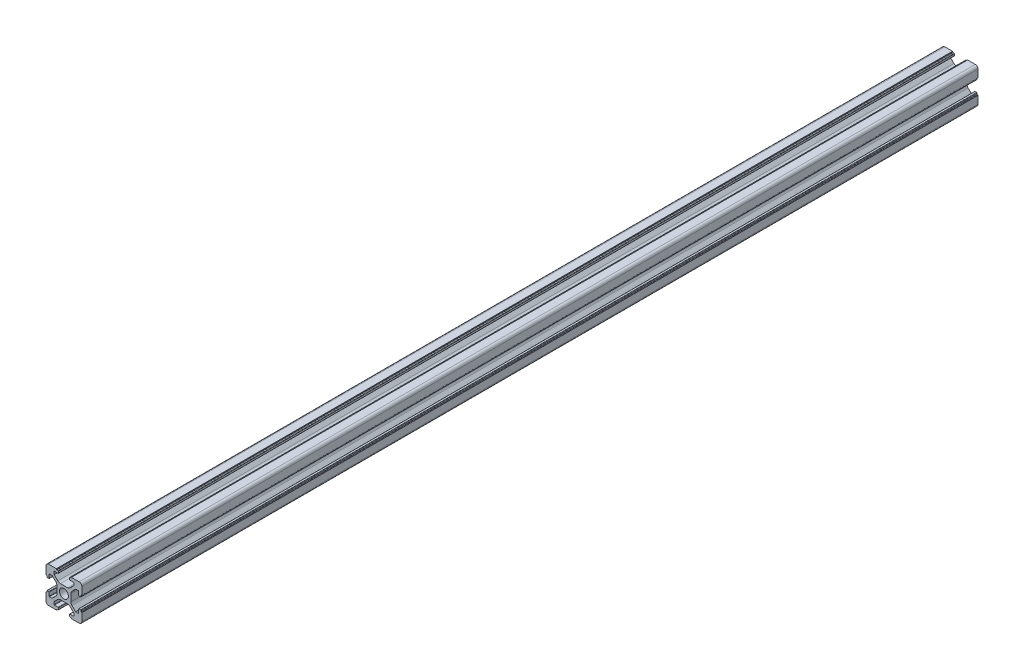
SolidWorks part; units mm, degrees
material "6063-T5"
ref_plane "Front Plane" through (0, 0, 0) normal (0, 0, 1) x (1, 0, 0)
ref_plane "Top Plane" through (0, 0, 0) normal (0, 1, 0) x (1, 0, 0)
ref_plane "Right Plane" through (0, 0, 0) normal (1, 0, 0) x (0, 0, -1)
sketch "Sketch1" plane through (0, 0, 0) normal (0, 0, -1) x (1, 0, 0)
  line L0 (1.5, 0) -> (5.8, 0)
  line L1 (20, 1.5) -> (20, 5.8)
  line L2 (18.5, 20) -> (14.2, 20)
  line L3 (0, 18.5) -> (0, 14.2)
  line L4 (14.2, 0) -> (18.5, 0)
  line L5 (13.3, 18.2) -> (15.3, 18.2)
  line L6 (20, 14.2) -> (20, 18.5)
  line L7 (0, 5.8) -> (0, 1.5)
  line L8 (6.7, 18.2) -> (4.7, 18.2)
  line L9 (1.8, 13.3) -> (1.8, 15.3)
  line L10 (19.3, 13.1) -> (18.4, 13.1)
  line L11 (19.3, 6.9) -> (18.4, 6.9)
  line L12 (6.9, 19.3) -> (6.9, 18.4)
  line L13 (13.1, 19.3) -> (13.1, 18.4)
  line L14 (0.7, 13.1) -> (1.6, 13.1)
  line L15 (0.7, 6.9) -> (1.6, 6.9)
  line L16 (13.4251, 14.4858) -> (15.4121, 16.4728)
  line L17 (14.4858, 13.4251) -> (16.4728, 15.4121)
  line L18 (14.4858, 6.5749) -> (16.4728, 4.5879)
  line L19 (13.4251, 5.5142) -> (15.4121, 3.5272)
  line L20 (6.5749, 5.5142) -> (4.5879, 3.5272)
  line L21 (5.5142, 6.5749) -> (3.5272, 4.5879)
  line L22 (5.5142, 13.4251) -> (3.5272, 15.4121)
  line L23 (6.5749, 14.4858) -> (4.5879, 16.4728)
  line L24 (6.9, 0.7) -> (6.9, 1.6)
  line L25 (13.1, 0.7) -> (13.1, 1.6)
  line L26 (5.8, 20) -> (1.5, 20)
  line L27 (1.8, 6.7) -> (1.8, 4.7)
  line L28 (6.7, 1.8) -> (4.7, 1.8)
  line L29 (13.3, 1.8) -> (15.3, 1.8)
  line L30 (18.2, 13.3) -> (18.2, 15.3)
  line L31 (18.2, 6.7) -> (18.2, 4.7)
  line L32 (2, 4.5) -> (3.3151, 4.5)
  line L33 (2, 15.5) -> (3.3151, 15.5)
  line L34 (4.5, 18) -> (4.5, 16.6849)
  line L35 (15.5, 18) -> (15.5, 16.6849)
  line L36 (18, 15.5) -> (16.6849, 15.5)
  line L37 (4.5, 2) -> (4.5, 3.3151)
  line L38 (15.5, 2) -> (15.5, 3.3151)
  line L39 (18, 4.5) -> (16.6849, 4.5)
  line L40 (7.9891, 13.9) -> (12.0109, 13.9)
  line L41 (7.9891, 6.1) -> (12.0109, 6.1)
  line L42 (13.9, 12.0109) -> (13.9, 7.9891)
  line L43 (6.1, 12.0109) -> (6.1, 7.9891)
  line L44 (19.5, 6.7) -> (19.5, 6.1)
  line L45 (5.9, 19.9) -> (5.9, 19.7)
  line L46 (6.1, 19.5) -> (6.7, 19.5)
  line L47 (14.1, 19.9) -> (14.1, 19.7)
  line L48 (13.9, 19.5) -> (13.3, 19.5)
  line L49 (0.1, 14.1) -> (0.3, 14.1)
  line L50 (0.5, 13.9) -> (0.5, 13.3)
  line L51 (0.1, 5.9) -> (0.3, 5.9)
  line L52 (0.5, 6.1) -> (0.5, 6.7)
  line L53 (19.9, 14.1) -> (19.7, 14.1)
  line L54 (19.5, 13.9) -> (19.5, 13.3)
  line L55 (19.7, 5.9) -> (19.9, 5.9)
  line L56 (14.1, 0.1) -> (14.1, 0.3)
  line L57 (13.9, 0.5) -> (13.3, 0.5)
  line L58 (6.7, 0.5) -> (6.1, 0.5)
  line L59 (5.9, 0.3) -> (5.9, 0.1)
  circle A0 centre (10, 10) radius 2.5
  arc A1 (18.5, 0) -> (20, 1.5) centre (18.5, 1.5) ccw
  arc A2 (1.5, 0) -> (0, 1.5) centre (1.5, 1.5) cw
  arc A3 (20, 18.5) -> (18.5, 20) centre (18.5, 18.5) ccw
  arc A4 (1.5, 20) -> (0, 18.5) centre (1.5, 18.5) ccw
  arc A5 (12.0109, 6.1) -> (13.4251, 5.5142) centre (12.0109, 4.1) cw
  arc A6 (13.9, 7.9891) -> (14.4858, 6.5749) centre (15.9, 7.9891) ccw
  arc A7 (13.9, 12.0109) -> (14.4858, 13.4251) centre (15.9, 12.0109) cw
  arc A8 (12.0109, 13.9) -> (13.4251, 14.4858) centre (12.0109, 15.9) ccw
  arc A9 (7.9891, 13.9) -> (6.5749, 14.4858) centre (7.9891, 15.9) cw
  arc A10 (6.1, 7.9891) -> (5.5142, 6.5749) centre (4.1, 7.9891) cw
  arc A11 (6.1, 12.0109) -> (5.5142, 13.4251) centre (4.1, 12.0109) ccw
  arc A12 (13.1, 1.6) -> (13.3, 1.8) centre (13.3, 1.6) cw
  arc A13 (6.9, 1.6) -> (6.7, 1.8) centre (6.7, 1.6) ccw
  arc A14 (6.1, 0.5) -> (5.9, 0.3) centre (6.1, 0.3) ccw
  arc A15 (6.7, 0.5) -> (6.9, 0.7) centre (6.7, 0.7) ccw
  arc A16 (1.6, 6.9) -> (1.8, 6.7) centre (1.6, 6.7) cw
  arc A17 (0.5, 6.7) -> (0.7, 6.9) centre (0.7, 6.7) cw
  arc A18 (0.5, 13.3) -> (0.7, 13.1) centre (0.7, 13.3) ccw
  arc A19 (1.6, 13.1) -> (1.8, 13.3) centre (1.6, 13.3) ccw
  arc A20 (6.7, 19.5) -> (6.9, 19.3) centre (6.7, 19.3) cw
  arc A21 (6.9, 18.4) -> (6.7, 18.2) centre (6.7, 18.4) cw
  arc A22 (13.1, 18.4) -> (13.3, 18.2) centre (13.3, 18.4) ccw
  arc A23 (13.3, 19.5) -> (13.1, 19.3) centre (13.3, 19.3) ccw
  arc A24 (18.4, 13.1) -> (18.2, 13.3) centre (18.4, 13.3) cw
  arc A25 (19.5, 13.3) -> (19.3, 13.1) centre (19.3, 13.3) cw
  arc A26 (19.5, 6.7) -> (19.3, 6.9) centre (19.3, 6.7) ccw
  arc A27 (14.1, 0.3) -> (13.9, 0.5) centre (13.9, 0.3) ccw
  arc A28 (19.5, 6.1) -> (19.7, 5.9) centre (19.7, 6.1) ccw
  arc A29 (5.9, 19.7) -> (6.1, 19.5) centre (6.1, 19.7) ccw
  arc A30 (14.1, 19.7) -> (13.9, 19.5) centre (13.9, 19.7) cw
  arc A31 (19.7, 14.1) -> (19.5, 13.9) centre (19.7, 13.9) ccw
  arc A32 (13.3, 0.5) -> (13.1, 0.7) centre (13.3, 0.7) cw
  arc A33 (0.3, 14.1) -> (0.5, 13.9) centre (0.3, 13.9) cw
  arc A34 (0.3, 5.9) -> (0.5, 6.1) centre (0.3, 6.1) ccw
  arc A35 (0, 5.8) -> (0.1, 5.9) centre (0.1, 5.8) cw
  arc A36 (5.9, 0.1) -> (5.8, 0) centre (5.8, 0.1) cw
  arc A37 (14.1, 0.1) -> (14.2, 0) centre (14.2, 0.1) ccw
  arc A38 (19.9, 5.9) -> (20, 5.8) centre (19.9, 5.8) cw
  arc A39 (20, 14.2) -> (19.9, 14.1) centre (19.9, 14.2) cw
  arc A40 (14.2, 20) -> (14.1, 19.9) centre (14.2, 19.9) ccw
  arc A41 (5.8, 20) -> (5.9, 19.9) centre (5.8, 19.9) cw
  arc A42 (0, 14.2) -> (0.1, 14.1) centre (0.1, 14.2) ccw
  arc A43 (18.4, 6.9) -> (18.2, 6.7) centre (18.4, 6.7) ccw
  arc A44 (1.8, 15.3) -> (2, 15.5) centre (2, 15.3) cw
  arc A45 (1.8, 4.7) -> (2, 4.5) centre (2, 4.7) ccw
  arc A46 (4.7, 1.8) -> (4.5, 2) centre (4.7, 2) cw
  arc A47 (15.3, 1.8) -> (15.5, 2) centre (15.3, 2) ccw
  arc A48 (18.2, 4.7) -> (18, 4.5) centre (18, 4.7) cw
  arc A49 (18.2, 15.3) -> (18, 15.5) centre (18, 15.3) ccw
  arc A50 (15.3, 18.2) -> (15.5, 18) centre (15.3, 18) cw
  arc A51 (4.7, 18.2) -> (4.5, 18) centre (4.7, 18) ccw
  arc A52 (7.9891, 6.1) -> (6.5749, 5.5142) centre (7.9891, 4.1) ccw
  arc A53 (3.3151, 15.5) -> (3.5272, 15.4121) centre (3.3151, 15.2) cw
  arc A54 (4.5, 16.6849) -> (4.5879, 16.4728) centre (4.8, 16.6849) ccw
  arc A55 (15.5, 16.6849) -> (15.4121, 16.4728) centre (15.2, 16.6849) cw
  arc A56 (16.6849, 15.5) -> (16.4728, 15.4121) centre (16.6849, 15.2) ccw
  arc A57 (16.6849, 4.5) -> (16.4728, 4.5879) centre (16.6849, 4.8) cw
  arc A58 (15.5, 3.3151) -> (15.4121, 3.5272) centre (15.2, 3.3151) ccw
  arc A59 (4.5, 3.3151) -> (4.5879, 3.5272) centre (4.8, 3.3151) cw
  arc A60 (3.3151, 4.5) -> (3.5272, 4.5879) centre (3.3151, 4.8) ccw
  point P67 (0, 0)
  point P125 (14.1, 19.5)
extrude "Boss-Extrude1" add sketch "Sketch1" along normal blind 500 contours L23 A54 L34 A51 L8 A21 L12 A20 L46 A29 L45 A41 L26 A4 L3 A42 L49 A33 L50 A18 L14 A19 L9 A44 L33 A53 L22 A11 L43 A10 L21 A60 L32 A45 L27 A16 L15 A17 L52 A34 L51 A35 L7 A2 L0 A36 L59 A14 L58 A15 L24 A13 L28 A46 L37 A59 L20 A52 L41 A5 L19 A58 L38 A47 L29 A12 L25 A32 L57 A27 L56 A37 L4 A1 L1 A38 L55 A28 L44 A26 L11 A43 L31 A48 L39 A57 L18 A6 L42 A7 L17 A56 L36 A49 L30 A24 L10 A25 L54 A31 L53 A39 L6 A3 L2 A40 L47 A30 L48 A23 L13 A22 L5 A50 L35 A55 L16 A8 L40 A9 | A0
ref_plane "topMidPlane" through (0, -10, 0) normal (0, -1, 0) x (-1, 0, 0)
ref_plane "Plane2" through (10, 0, 0) normal (-1, 0, 0) x (0, 0, 1)
ref_plane "midLength" through (0, 0, -250) normal (0, 0, 1) x (1, 0, 0)
